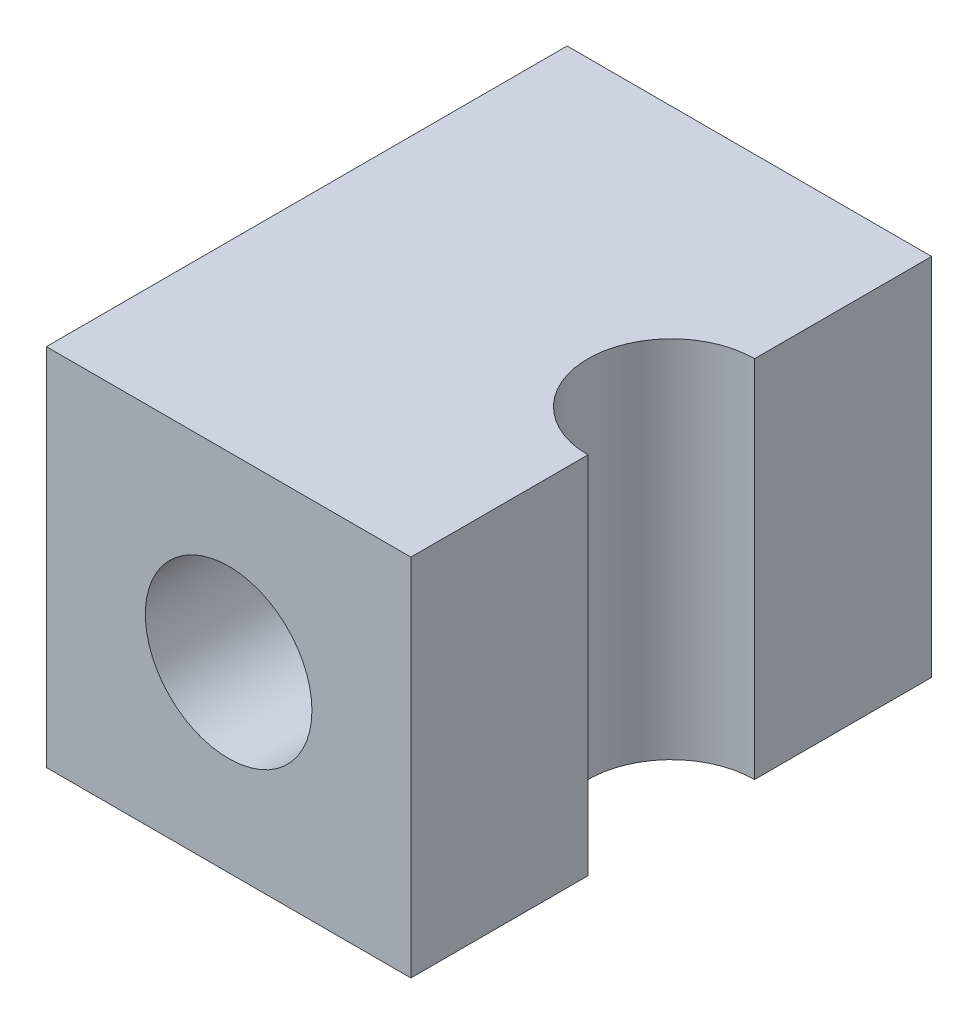
SolidWorks part; units mm, degrees
material "ABS"
ref_plane "Front Plane" through (0, 0, 0) normal (0, 0, 1) x (1, 0, 0)
ref_plane "Top Plane" through (0, 0, 0) normal (0, 1, 0) x (1, 0, 0)
ref_plane "Right Plane" through (0, 0, 0) normal (1, 0, 0) x (0, 0, -1)
sketch "Sketch1" plane through (0, 0, 0) normal (0, 0, 1) x (1, 0, 0)
  line L1 (-3.5, 3.5) -> (3.5, 3.5)
  line L2 (-3.5, 3.5) -> (-3.5, -3.5)
  line L3 (-3.5, -3.5) -> (3.5, -3.5)
  line L4 (3.5, 3.5) -> (3.5, -3.5)
  line L5 (-3.5, 3.5) -> (3.5, -3.5) construction
  line L6 (-3.5, -3.5) -> (3.5, 3.5) construction
  circle A0 centre (0, 0) radius 1.6
  point P0 (0, 0)
  dimension "D2" = 3.2
  dimension "D1" = 7
extrude "Boss-Extrude1" add sketch "Sketch1" along normal mid plane 10
sketch "Sketch2" plane through (0, 3.5, 0) normal (0, 1, 0) x (1, 0, 0)
  line L1 (3.5, 0) -> (0, 0) construction
  circle A0 centre (3.5, 0) radius 1.6
  dimension "D1" = 3.2
  dimension "D2" = 3.5
extrude "Cut-Extrude1" cut sketch "Sketch2" against normal through all
